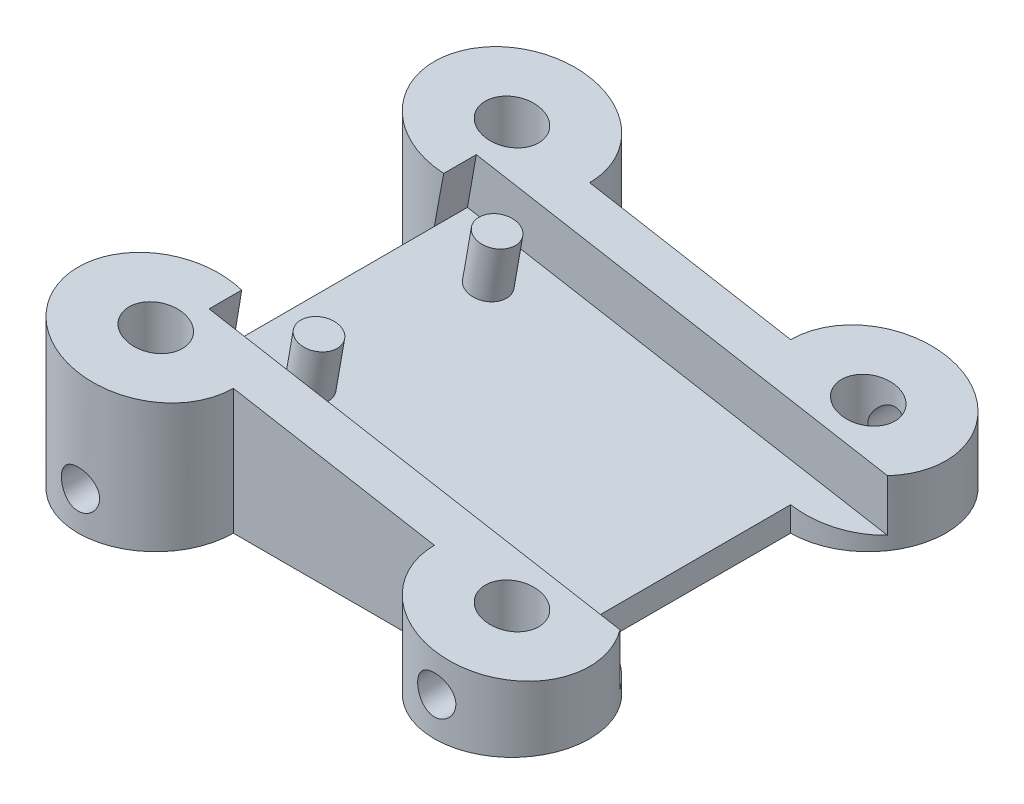
SolidWorks part; units mm, degrees
ref_plane "Front Plane" through (0, 0, 0) normal (0, 0, 1) x (1, 0, 0)
ref_plane "Top Plane" through (0, 0, 0) normal (0, 1, 0) x (1, 0, 0)
ref_plane "Right Plane" through (0, 0, 0) normal (1, 0, 0) x (0, 0, -1)
sketch "Sketch1" plane through (0, 0, 0) normal (0, 1, 0) x (1, 0, 0)
  line L0 (14, 28) -> (14, 0) construction
  line L1 (0, 0) -> (28, 0)
  line L2 (0, 0) -> (0, 28)
  line L3 (0, 28) -> (28, 28)
  line L4 (28, 0) -> (28, 28)
  line L5 (0, 14) -> (28, 14) construction
  point P9 (14, 14)
  dimension "D1" = 28
extrude "Boss-Extrude1" add sketch "Sketch1" along normal blind 10.9372
sketch "Sketch2" plane through (0, 0, 0) normal (0, 0, 1) x (1, 0, 0)
  line L0 (0, 10.9372) -> (28, 6)
  line L1 (0, 10.9372) -> (28, 10.9372) construction
  line L2 (28, 10.9372) -> (28, 0) construction
  line L3 (0, 10.9372) -> (28, 10.9372)
  line L4 (28, 10.9372) -> (28, 6)
  dimension "D2" = 6
  dimension "D3" = 10
extrude "Cut-Extrude1" cut sketch "Sketch2" against normal through all
sketch "Sketch3" plane through (1.8704, 10.6074, 0) normal (0.1736, 0.9848, 0) x (0.9848, -0.1736, 0)
  line L0 (-1.8992, 28) -> (-1.8992, 0) construction
  line L1 (-1.8992, 3.5) -> (48.1008, 3.5)
  line L2 (-1.8992, 3.5) -> (-1.8992, 24.5)
  line L3 (-1.8992, 24.5) -> (48.1008, 24.5)
  line L4 (48.1008, 3.5) -> (48.1008, 24.5)
  point P9 (-1.8992, 14)
  point P10 (-1.8992, 14)
  dimension "D1" = 21
  dimension "D2" = 50
extrude "Cut-Extrude2" cut sketch "Sketch3" against normal blind 4
ref_plane "Plane1" through (0, 10.9372, 0) normal (0, 1, 0) x (1, 0, 0)
sketch "Sketch11" plane through (1.1758, 6.6681, 0) normal (0.1736, 0.9848, 0) x (0.9848, -0.1736, 0)
  line L0 (27.238, 24.5) -> (-1.1939, 24.5) construction
  line L1 (27.238, 24.5) -> (27.238, 3.5) construction
  line L2 (-1.1939, 3.5) -> (27.238, 3.5) construction
  line L3 (27.238, 24.5) -> (-1.1939, 24.5) construction
  line L4 (27.238, 24.5) -> (27.238, 3.5) construction
  line L5 (-1.1939, 3.5) -> (27.238, 3.5) construction
  line L6 (13.0221, 3) -> (13.0221, 50003) construction
  line L7 (24.633, 14) -> (-49975.367, 14) construction
  circle A2 centre (4.0221, 21) radius 1.45
  circle A3 centre (4.0221, 7) radius 1.45
  point P6 (13.0221, 3.5)
  point P9 (27.238, 14)
  dimension "D4" = 2.9
  dimension "D5" = 9
  dimension "D6" = 7
extrude "Boss-Extrude2" add sketch "Sketch11" along normal blind 4
sketch "Sketch12" plane through (0, 10.9372, 0) normal (0, 1, 0) x (1, 0, 0)
  line L0 (0, 3.5) -> (0, 24.5) construction
  line L1 (0, 3.5) -> (28, 3.5) construction
  line L2 (0, 3.5) -> (0, 24.5) construction
  line L3 (0, 3.5) -> (28, 3.5) construction
  line L4 (0, 14) -> (50000, 14) construction
  line L5 (14, 4) -> (14, 50004) construction
  circle A0 centre (14, 14) radius 7
  point P7 (0, 14)
  point P10 (14, 3.5)
  dimension "D1" = 14
sketch "Sketch13" plane through (0, 0, 0) normal (0, -1, 0) x (1, 0, 0)
  line L0 (0, 0) -> (28, 0) construction
  line L1 (28, 0) -> (28, -28) construction
  line L2 (28, -28) -> (0, -28) construction
  line L3 (0, -28) -> (0, 0) construction
  line L4 (0, 0) -> (28, 0) construction
  line L5 (28, 0) -> (28, -28) construction
  line L6 (28, -28) -> (0, -28) construction
  line L7 (0, -28) -> (0, 0) construction
  line L8 (0, -14) -> (28, -14) construction
  line L9 (14, -28) -> (14, 0) construction
  circle A0 centre (0, 0) radius 2.1
  circle A1 centre (28, 0) radius 2.1
  circle A2 centre (28, -28) radius 2.1
  circle A3 centre (0, -28) radius 2.1
  dimension "D1" = 4.2
  dimension "D2" = 2
  dimension "D3" = 2
extrude "Cut-Extrude5" cut sketch "Sketch13" against normal through all
sketch "Sketch14" plane through (0, 0, 0) normal (0, -1, 0) x (1, 0, 0)
  line L0 (28, -3.5) -> (28, -2.1) construction
  line L1 (2.1, -28) -> (25.9, -28) construction
  line L2 (0, -3.5) -> (0, -24.5) construction
  circle A0 centre (0, 0) radius 2.1 construction
  circle A1 centre (0, 0) radius 2.1 construction
  circle A2 centre (0, 0) radius 6.1
  circle A3 centre (0, 0) radius 2.1
  circle A4 centre (28, 0) radius 2.1
  circle A5 centre (28, 0) radius 6.1
  circle A6 centre (28, -28) radius 2.1
  circle A7 centre (28, -28) radius 6.1
  circle A8 centre (0, -28) radius 2.1
  circle A9 centre (0, -28) radius 6.1
  dimension "D1" = 4
  dimension "D4" = 4.2
  dimension "D2" = 2
  dimension "D3" = 2
extrude "Boss-Extrude3" add sketch "Sketch14" against normal up to surface (10.9372 mm away)
sketch "Sketch15" plane through (0, 0, -28) normal (0, 0, -1) x (-1, 0, 0)
  line L0 (-21.9, 0) -> (-6.1, 0) construction
  line L1 (-21.9, 0) -> (-0.9, 0) construction
  line L4 (-14, 8.4686) -> (-14, 0) construction
  line L5 (-6.1, 9.8616) -> (-21.9, 7.0756) construction
  circle A0 centre (-28, 3) radius 1.5
  circle A1 centre (0, 3) radius 1.5
  point P4 (-28, 0)
  dimension "D1" = 3
  dimension "D2" = 3
extrude "Cut-Extrude6" cut sketch "Sketch15" along normal through all
sketch "Sketch16" plane through (0, 0, 0) normal (0, 0, 1) x (1, 0, 0)
  circle A0 centre (0, 3) radius 1.5 construction
  circle A1 centre (28, 3) radius 1.5 construction
  circle A2 centre (0, 3) radius 1.5
  circle A3 centre (28, 3) radius 1.5
extrude "Cut-Extrude7" cut sketch "Sketch16" along normal through all
sketch "Sketch18" plane through (1.8704, 10.6074, 0) normal (0.1736, 0.9848, 0) x (0.9848, -0.1736, 0)
  line L5 (-1.8992, 3.5) -> (25.6754, 3.5) construction
  line L8 (3.1739, 3.5) -> (21.4597, 3.5) construction
  line L9 (3.1739, 3.5) -> (21.4597, 3.5) construction
  line L22 (3.8792, 24.5) -> (-1.1939, 24.5)
  line L37 (6.4597, 3.5) -> (36.4597, 3.5)
  line L38 (6.4597, 3.5) -> (6.4597, 24.5)
  line L39 (6.4597, 24.5) -> (36.4597, 24.5)
  line L40 (36.4597, 3.5) -> (36.4597, 24.5)
  line L42 (-1.1939, 24.5) -> (-1.1939, 21.9)
  line L46 (-1.1939, 6.1) -> (-1.1939, 3.5)
  line L47 (-1.1939, 3.5) -> (3.8792, 3.5)
  line L49 (3.1739, 24.5) -> (21.4597, 24.5) construction
  ellipse E1 centre (-1.1939, 28) end of major axis (5.0002, 28) minor radius 6.1 (-1.1939, 21.9) -> (3.8792, 24.5) ccw construction
  ellipse E2 centre (-1.1939, 28) end of major axis (5.0002, 28) minor radius 6.1 (-1.1939, 21.9) -> (3.8792, 24.5) ccw
  ellipse E3 centre (-1.1939, 0) end of major axis (5.0002, 0) minor radius 6.1 (3.8792, 3.5) -> (-1.1939, 6.1) ccw construction
  ellipse E4 centre (-1.1939, 0) end of major axis (5.0002, 0) minor radius 6.1 (3.8792, 3.5) -> (-1.1939, 6.1) ccw
  point P7 (21.4597, 3.5)
  dimension "D1" = 30
extrude "Cut-Extrude8" cut sketch "Sketch18" against normal up to surface (4 mm away) up to face at (6.5647, 5.7179, -21)
equation "\"TrackLength\"= 150"
equation "\"MarbleWidth\"= 13"
equation "\"MarbleTrackWidth\"= \"MarbleWidth\" - 1"
equation "\"TrackWidth\"= \"MarbleTrackWidth\" + ( 2 * 4 )"
equation "\"MarbleTrackLength\"= \"TrackLength\" - ( 2 * 8 )"
equation "\"MountWidth\"= \"TrackWidth\" + 8"
equation "\"D1@Sketch1\"=\"MountWidth\""
equation "\"D1@Boss-Extrude1\"=\"RampHeight\""
equation "\"RampDepth\"=6"
equation "\"RampAngle\"= 10"
equation "\"RampHeight\"= ( \"MountWidth\" * tan ( \"RampAngle\" ) ) + \"RampDepth\""
equation "\"D1@Sketch3\"=\"TrackWidth\" + 1"
equation "\"MountWidth\"= \"TrackWidth\" + 10"
equation "\"MountLength\"=66.6651"
